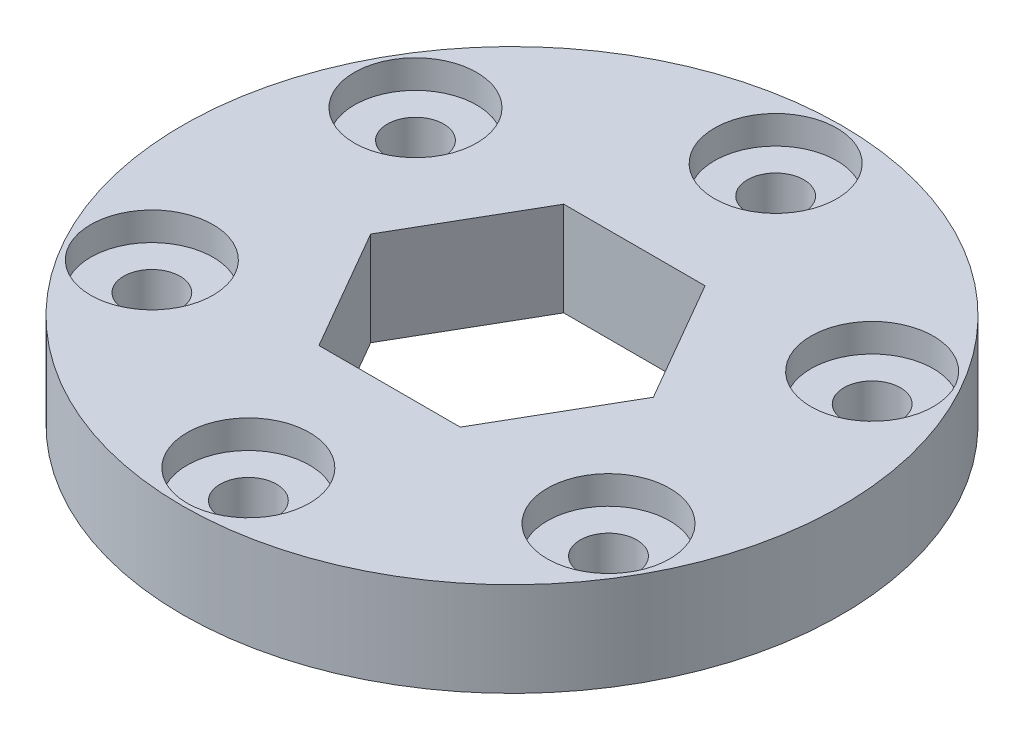
SolidWorks part; units mm, degrees
ref_plane "Front Plane" through (0, 0, 0) normal (0, 0, 1) x (1, 0, 0)
ref_plane "Top Plane" through (0, 0, 0) normal (0, 1, 0) x (1, 0, 0)
ref_plane "Right Plane" through (0, 0, 0) normal (1, 0, 0) x (0, 0, -1)
sketch "Sketch1" plane through (0, 0, 0) normal (0, 1, 0) x (1, 0, 0)
  line L1 (7.5056, 0) -> (3.7528, 6.5)
  line L2 (3.7528, 6.5) -> (-3.7528, 6.5)
  line L3 (-3.7528, 6.5) -> (-7.5056, 0)
  line L4 (-7.5056, 0) -> (-3.7528, -6.5)
  line L5 (-3.7528, -6.5) -> (3.7528, -6.5)
  line L6 (3.7528, -6.5) -> (7.5056, 0)
  circle A0 centre (0, 0) radius 17.5
  circle A1 centre (0, 0) radius 14 construction
  circle A2 centre (0, 0) radius 6.5 construction
  circle A3 centre (0, 14) radius 1.5
  circle A4 centre (12.1244, 7) radius 1.5
  circle A5 centre (12.1244, -7) radius 1.5
  circle A6 centre (0, -14) radius 1.5
  circle A7 centre (-12.1244, -7) radius 1.5
  circle A8 centre (-12.1244, 7) radius 1.5
  point P26 (0, 0)
  dimension "D1" = 35
  dimension "D2" = 28
  dimension "D4" = 3
  dimension "D3" = 13
  dimension "D5" = 6
extrude "Boss-Extrude1" add sketch "Sketch1" along normal blind 5
sketch "Sketch2" plane through (0, 5, 0) normal (0, 1, 0) x (1, 0, 0)
  circle A0 centre (0, 0) radius 14 construction
  circle A1 centre (0, 14) radius 3.25
  circle A2 centre (12.1244, 7) radius 3.25
  circle A3 centre (12.1244, -7) radius 3.25
  circle A4 centre (0, -14) radius 3.25
  circle A5 centre (-12.1244, -7) radius 3.25
  circle A6 centre (-12.1244, 7) radius 3.25
  point P18 (0, 0)
  dimension "D1" = 6.5
  dimension "D2" = 6
extrude "Cut-Extrude1" cut sketch "Sketch2" against normal blind 1.5
